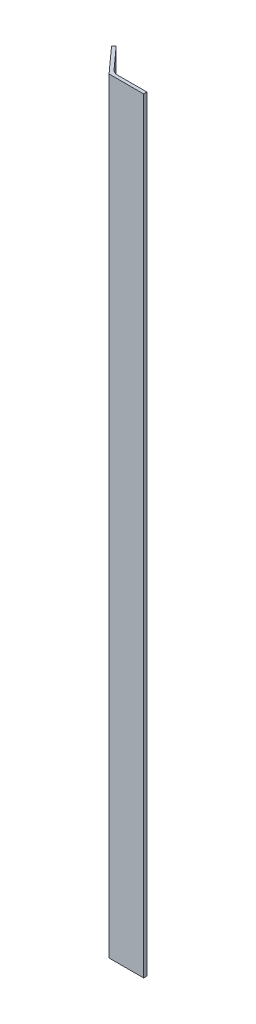
SolidWorks part; units mm, degrees
ref_plane "Спереди" through (0, 0, 0) normal (0, 0, 1) x (1, 0, 0)
ref_plane "Сверху" through (0, 0, 0) normal (0, 1, 0) x (1, 0, 0)
ref_plane "Справа" through (0, 0, 0) normal (1, 0, 0) x (0, 0, -1)
sketch "Эскиз1" plane through (0, 0, 0) normal (0, 1, 0) x (1, 0, 0)
  line L0 (-18.0829, 14.0427) -> (-16.5982, 15.3827)
  line L1 (-0.9318, 0.4869) -> (17.1228, 0.4869)
  line L2 (-16.5982, 15.3827) -> (-4.6436, 2.1369)
  line L3 (-18.0829, 14.0427) -> (-4.0435, -1.5131)
  line L4 (-4.0435, -1.5131) -> (17.1228, -1.5131)
  line L5 (17.1228, -1.5131) -> (17.1228, 0.4869)
  arc A0 (-0.9318, 0.4869) -> (-4.6436, 2.1369) centre (-0.9318, 5.4869) cw
  dimension "D1" = 5
extrude "Вытянуть1" add sketch "Эскиз1" along normal up to surface (468.2137 mm away) from offset 40
